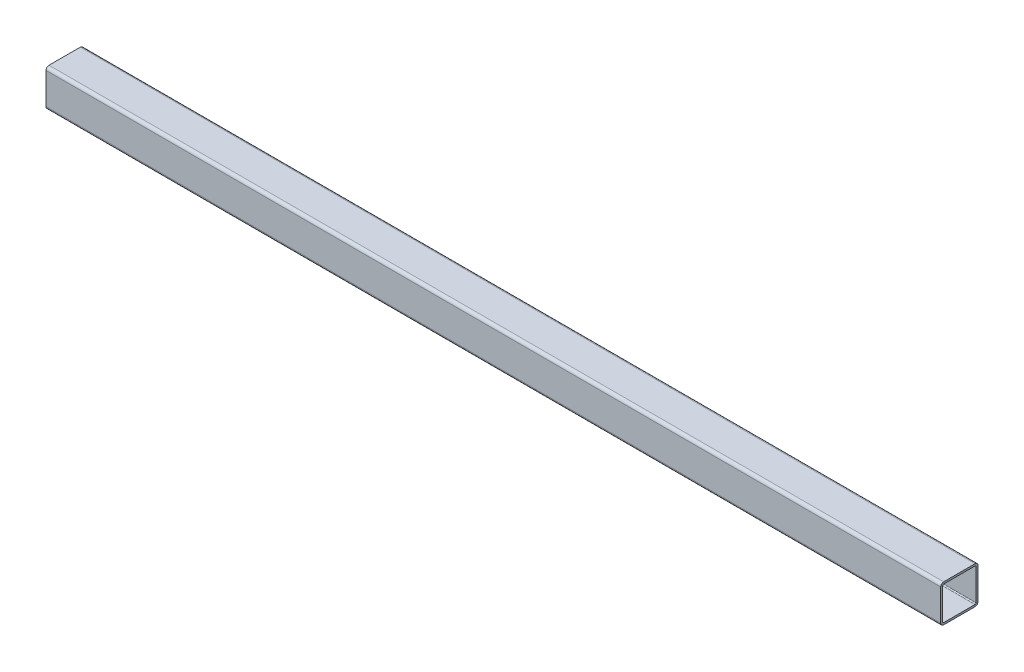
SolidWorks part; units mm, degrees
material "Plain Carbon Steel"
ref_plane "Front Plane" through (0, 0, 0) normal (0, 0, 1) x (1, 0, 0)
ref_plane "Top Plane" through (0, 0, 0) normal (0, 1, 0) x (1, 0, 0)
ref_plane "Right Plane" through (0, 0, 0) normal (1, 0, 0) x (0, 0, -1)
sketch "Sketch1" plane through (0, 0, 0) normal (1, 0, 0) x (0, 0, -1)
  line L0 (0, 2.54) -> (0, 29.21)
  line L1 (-2.54, 31.75) -> (-29.21, 31.75)
  line L2 (-31.75, 29.21) -> (-31.75, 2.54)
  line L3 (-29.21, 0) -> (-2.54, 0)
  line L4 (-1.651, 2.54) -> (-1.651, 29.21)
  line L5 (-2.54, 30.099) -> (-29.21, 30.099)
  line L6 (-30.099, 29.21) -> (-30.099, 2.54)
  line L7 (-29.21, 1.651) -> (-2.54, 1.651)
  arc A0 (-31.75, 2.54) -> (-29.21, 0) centre (-29.21, 2.54) ccw
  arc A1 (0, 2.54) -> (-2.54, 0) centre (-2.54, 2.54) cw
  arc A2 (0, 29.21) -> (-2.54, 31.75) centre (-2.54, 29.21) ccw
  arc A3 (-31.75, 29.21) -> (-29.21, 31.75) centre (-29.21, 29.21) cw
  arc A4 (-1.651, 29.21) -> (-2.54, 30.099) centre (-2.54, 29.21) ccw
  arc A5 (-30.099, 29.21) -> (-29.21, 30.099) centre (-29.21, 29.21) cw
  arc A6 (-30.099, 2.54) -> (-29.21, 1.651) centre (-29.21, 2.54) ccw
  arc A7 (-1.651, 2.54) -> (-2.54, 1.651) centre (-2.54, 2.54) cw
  point P12 (0, 0)
  point P15 (0, 31.75)
  point P18 (-31.75, 31.75)
  dimension "D3" = 2.54
  dimension "D1" = 31.75
  dimension "D2" = 31.75
  dimension "D4" = 1.651
extrude "Boss-Extrude1" add sketch "Sketch1" along normal blind 304.8
scale "Scale1" scale about centroid uniform scaling no x scale factor 1 y scale factor 0.4 z scale factor 0.4
